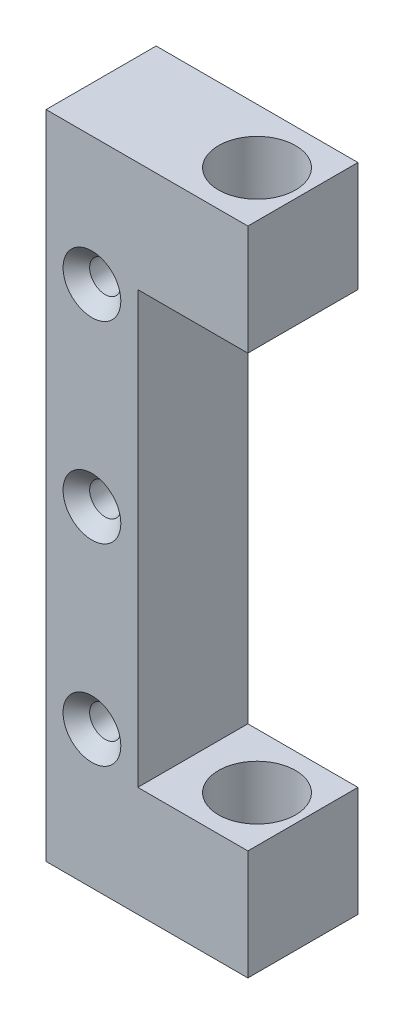
SolidWorks part; units mm, degrees
ref_plane "Ebene vorne" through (0, 0, 0) normal (0, 0, 1) x (1, 0, 0)
ref_plane "Ebene oben" through (0, 0, 0) normal (0, 1, 0) x (1, 0, 0)
ref_plane "Ebene rechts" through (0, 0, 0) normal (1, 0, 0) x (0, 0, -1)
sketch "Skizze1" plane through (0, 0, 0) normal (0, 0, 1) x (1, 0, 0)
  line L0 (0, 0) -> (0, 71)
  line L1 (0, 71) -> (22, 71)
  line L2 (22, 71) -> (22, 59)
  line L3 (22, 59) -> (10, 59)
  line L4 (10, 59) -> (10, 12)
  line L7 (0, 0) -> (22, 0)
  line L8 (22, 0) -> (22, 12)
  line L9 (22, 12) -> (10, 12)
  dimension "D1" = 22
  dimension "D2" = 71
  dimension "D3" = 12
  dimension "D4" = 10
  dimension "D5" = 12
extrude "Aufsatz-Linear austragen1" add sketch "Skizze1" along normal blind 12
hole_wizard "Formsenkung für M3 Linsensenkschraube mit Schlitz2" positions "Skizze8" profile "Skizze9" countersink size "M3" standard "DIN" end condition through all
sketch "Skizze8" plane through (0, 0, 12) normal (0, 0, 1) x (1, 0, 0)
  point P0 (5, 57)
  point P2 (5, 36)
  point P22 (5, 15)
  dimension "D1" = 21
  dimension "D2" = 36
  dimension "D3" = 21
sketch "Skizze9" plane through (5, 57, 12) normal (1, 0, 0) x (0, -1, 0)
  line L0 (0, 0) -> (0, 12)
  line L1 (0, 12) -> (1.7, 12)
  line L2 (1.7, 12) -> (1.7, 1.45)
  line L3 (1.7, 1.45) -> (3.15, 0)
  line L5 (3.15, 0) -> (0, 0)
  line L6 (-1.7, 1.45) -> (-3.15, 0) construction
  line L11 (0, -6.35) -> (0, 107.95) construction
  dimension "Bohrerdurchmesser" = 3.4
  dimension "Bohrungstiefe" = 12
  dimension "Senkdurchmesser (Oben)" = 6.3
  dimension "Senkwinkel (Oben)" = 90
hole_wizard "Ø8.4 (8.4) Durchmesser Bohrung3" positions "Skizze10" profile "Skizze11" hole size "Ø8.4" standard "DIN" end condition through all
sketch "Skizze10" plane through (0, 71, 0) normal (0, 1, 0) x (1, 0, 0)
  line L0 (22, -12) -> (22, 0) construction
  line L2 (22, -12) -> (0, -12) construction
  point P0 (17, -6)
  dimension "D1" = 5
  dimension "D2" = 6
sketch "Skizze11" plane through (17, 71, 6) normal (1, 0, 0) x (0, 0, 1)
  line L0 (0, 0) -> (0, 71)
  line L1 (0, 71) -> (4.2, 71)
  line L2 (4.2, 71) -> (4.2, 0)
  line L5 (4.2, 0) -> (0, 0)
  line L11 (0, -6.35) -> (0, 107.95) construction
  dimension "Bohrerdurchmesser" = 8.4
  dimension "Bohrungstiefe" = 71
